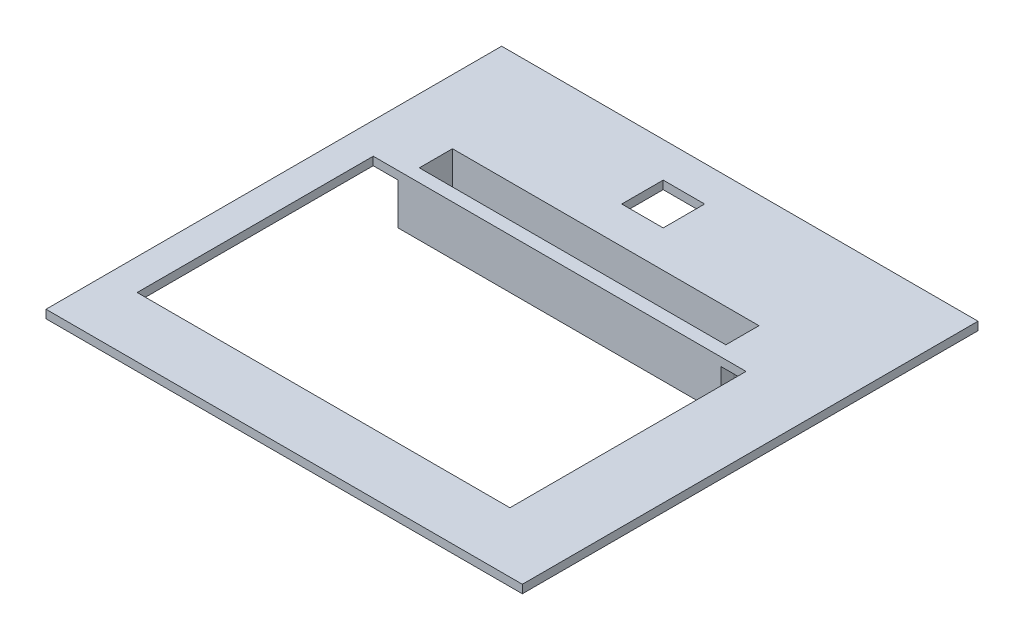
SolidWorks part; units mm, degrees
ref_plane "Front" through (0, 0, 0) normal (0, 0, 1) x (1, 0, 0)
ref_plane "Top" through (0, 0, 0) normal (0, 1, 0) x (1, 0, 0)
ref_plane "Right" through (0, 0, 0) normal (1, 0, 0) x (0, 0, -1)
sketch "Sketch2" plane through (0, 0, 0) normal (0, 1, 0) x (1, 0, 0)
  line L1 (57.5, 55) -> (-57.5, 55)
  line L2 (57.5, 55) -> (57.5, -55)
  line L3 (57.5, -55) -> (-57.5, -55)
  line L4 (-57.5, 55) -> (-57.5, -55)
  line L5 (57.5, 55) -> (-57.5, -55) construction
  line L6 (57.5, -55) -> (-57.5, 55) construction
  point P0 (0, 0)
  dimension "D1" = 110
  dimension "D2" = 115
extrude "Boss-Extrude1" add sketch "Sketch2" along normal blind 2
sketch "Sketch3" plane through (0, 2, 0) normal (0, 1, 0) x (1, 0, 0)
  line L0 (-57.5, -55) -> (57.5, -55) construction
  line L1 (-57.5, 55) -> (-57.5, -55) construction
  line L3 (-50, -40.5) -> (40, -40.5)
  line L4 (-50, -40.5) -> (-50, 16.5)
  line L5 (-50, 16.5) -> (40, 16.5)
  line L6 (40, -40.5) -> (40, 16.5)
  point P0 (-47, -44.5)
  point P5 (-47, -40.5)
  point P6 (-50, -40.5)
  dimension "D1" = 10.5
  dimension "D2" = 10.5
  dimension "D3" = 4
  dimension "D4" = 3
  dimension "D5" = 57
  dimension "D6" = 90
  dimension "D7" = 7.5
  dimension "D8" = 14.5
extrude "Cut-Extrude1" cut sketch "Sketch3" against normal through all both and the other way through all
sketch "Sketch4" plane through (0, 2, 0) normal (0, 1, 0) x (1, 0, 0)
  line L0 (-50, 16.5) -> (40, 16.5) construction
  line L1 (57.5, 55) -> (-57.5, 55) construction
  line L3 (-10, 40.75) -> (0, 40.75)
  line L4 (-10, 40.75) -> (-10, 30.75)
  line L5 (-10, 30.75) -> (0, 30.75)
  line L6 (0, 40.75) -> (0, 30.75)
  line L7 (-10, 40.75) -> (0, 30.75) construction
  line L8 (-10, 30.75) -> (0, 40.75) construction
  point P0 (-5, 16.5)
  point P1 (-5, 35.75)
  point P7 (-5, 35.75)
  dimension "D1" = 45
  dimension "D2" = 38.5
  dimension "D3" = 19.25
  dimension "D4" = 10
  dimension "D5" = 10
  dimension "D6" = 14.25
extrude "Cut-Extrude2" cut sketch "Sketch4" against normal blind 2
sketch "Sketch5" plane through (0, 2, 0) normal (0, 1, 0) x (1, 0, 0)
  line L0 (-10, 30.75) -> (0, 30.75) construction
  line L1 (-50, 16.5) -> (40, 16.5) construction
  line L2 (-57.5, 55) -> (-57.5, -55) construction
  line L3 (34, 19.625) -> (-44, 19.625)
  line L4 (34, 19.625) -> (34, 27.625)
  line L5 (34, 27.625) -> (-44, 27.625)
  line L6 (-44, 19.625) -> (-44, 27.625)
  line L7 (34, 19.625) -> (-44, 27.625) construction
  line L8 (34, 27.625) -> (-44, 19.625) construction
  line L9 (40, 16.5) -> (40, -40.5) construction
  line L10 (-50, -40.5) -> (-50, 16.5) construction
  point P0 (-5, 23.625)
  point P5 (-5, 23.625)
  dimension "D1" = 7.125
  dimension "D2" = 7.125
  dimension "D3" = 78
  dimension "D4" = 8
  dimension "D5" = 13.5
  dimension "D6" = 6
  dimension "D7" = 6
extrude "Cut-Extrude3" cut sketch "Sketch5" against normal through all
sketch "Sketch6" plane through (0, 0, 0) normal (0, -1, 0) x (-1, 0, 0)
  line L0 (-40, 16.5) -> (50, 16.5) construction
  line L1 (44, 19.625) -> (-34.0027, 19.625)
  line L2 (44, 19.625) -> (44, 16.5)
  line L3 (44, 16.5) -> (-34.0027, 16.5)
  line L4 (-34.0027, 19.625) -> (-34.0027, 16.5)
  dimension "D1" = 78.0027
extrude "Boss-Extrude3" add sketch "Sketch6" along normal blind 10
sketch "Sketch8" plane through (0, 0, 0) normal (0, -1, 0) x (-1, 0, 0)
  line L1 (-34, 27.625) -> (44, 27.625)
  line L2 (-34, 27.625) -> (-34, 28.625)
  line L3 (-34, 28.625) -> (44, 28.625)
  line L4 (44, 27.625) -> (44, 28.625)
  line L5 (-34, 28.625) -> (-19, 28.625)
  line L6 (-34, 28.625) -> (-34, 31.625)
  line L7 (-34, 31.625) -> (-19, 31.625)
  line L8 (-19, 28.625) -> (-19, 31.625)
  line L9 (44, 28.625) -> (29, 28.625)
  line L10 (44, 28.625) -> (44, 31.625)
  line L11 (44, 31.625) -> (29, 31.625)
  line L12 (29, 28.625) -> (29, 31.625)
  line L13 (44, 27.625) -> (42, 27.625)
  line L14 (44, 27.625) -> (44, 19.625)
  line L15 (44, 19.625) -> (42, 19.625)
  line L16 (42, 27.625) -> (42, 19.625)
  line L17 (-34, 27.625) -> (-32, 27.625)
  line L18 (-34, 27.625) -> (-34, 19.625)
  line L19 (-34, 19.625) -> (-32, 19.625)
  line L20 (-32, 27.625) -> (-32, 19.625)
  line M20 (-34, 27.625) -> (44, 27.625)
  dimension "D1" = 1
  dimension "D2" = 78
  dimension "D3" = 15
  dimension "D4" = 3
  dimension "D5" = 15
  dimension "D6" = 3
  dimension "D7" = 2
  dimension "D8" = 8
  dimension "D9" = 2
  dimension "D10" = 8
extrude "Boss-Extrude6" add sketch "Sketch8" along normal blind 10 contours L1 L4 L3 L2 M20 | L18 L17 L20 L19
sketch "Sketch10" plane through (0, 2, 0) normal (0, 1, 0) x (1, 0, 0)
  line L1 (34, 27.625) -> (32, 27.625)
  line L2 (34, 27.625) -> (34, 19.625)
  line L3 (34, 19.625) -> (32, 19.625)
  line L4 (32, 27.625) -> (32, 19.625)
  dimension "D1" = 8
  dimension "D2" = 2
extrude "Boss-Extrude7" add sketch "Sketch10" against normal blind 12
sketch "Sketch11" plane through (0, 2, 0) normal (0, 1, 0) x (1, 0, 0)
  line L0 (32, 27.625) -> (-44, 27.625) construction
  line L1 (-44, 19.625) -> (-42, 19.625)
  line L2 (-44, 19.625) -> (-44, 27.625)
  line L3 (-44, 27.625) -> (-42, 27.625)
  line L4 (-42, 19.625) -> (-42, 27.625)
  dimension "D1" = 8
  dimension "D2" = 2
extrude "Boss-Extrude8" add sketch "Sketch11" against normal blind 12
sketch "Sketch12" plane through (0, 0, 0) normal (0, -1, 0) x (-1, 0, 0)
  line L1 (-34, 28.625) -> (-19, 28.625)
  line L2 (-34, 28.625) -> (-34, 31.625)
  line L3 (-34, 31.625) -> (-19, 31.625)
  line L4 (-19, 28.625) -> (-19, 31.625)
  dimension "D1" = 15
  dimension "D2" = 3
extrude "Boss-Extrude9" add sketch "Sketch12" along normal blind 10
sketch "Sketch13" plane through (0, 0, 0) normal (0, -1, 0) x (-1, 0, 0)
  line L1 (44, 28.625) -> (29, 28.625)
  line L2 (44, 28.625) -> (44, 31.625)
  line L3 (44, 31.625) -> (29, 31.625)
  line L4 (29, 28.625) -> (29, 31.625)
  dimension "D1" = 15
  dimension "D2" = 3
extrude "Boss-Extrude10" add sketch "Sketch13" along normal blind 10
sketch "Sketch14" plane through (0, -10, 0) normal (0, -1, 0) x (-1, 0, 0)
  line L1 (-32, 19.625) -> (42, 19.625)
  line L2 (-32, 19.625) -> (-32, 27.625)
  line L3 (-32, 27.625) -> (42, 27.625)
  line L4 (42, 19.625) -> (42, 27.625)
extrude "Boss-Extrude11" add sketch "Sketch14" against normal blind 2 contours L2 L1 L4 L3
sketch "Sketch17" plane through (0, -8, 0) normal (0, 1, 0) x (1, 0, 0)
  line L0 (32, 19.625) -> (32, 27.625) construction
  line L1 (32, 27.625) -> (-42, 27.625) construction
  line L2 (-42, 19.625) -> (-42, 27.625) construction
  line L3 (32, 19.625) -> (-42, 19.625) construction
  circle A0 centre (25, 23.625) radius 2.375
  circle A1 centre (-35, 23.625) radius 2.375
  circle A2 centre (-26.43, 23.625) radius 2.375
  circle A3 centre (-17.86, 23.625) radius 2.375
  circle A4 centre (-0.72, 23.625) radius 2.375
  circle A5 centre (7.85, 23.625) radius 2.375
  circle A6 centre (16.42, 23.625) radius 2.375
  circle A7 centre (-9.29, 23.625) radius 2.375
  point P0 (25, 23.625)
  point P7 (-35, 23.625)
  point P12 (-26.43, 23.625)
  point P13 (-17.86, 23.625)
  point P14 (-0.72, 23.625)
  point P16 (7.85, 23.625)
  point P17 (16.42, 23.625)
  point P30 (-9.29, 23.625)
  dimension "D2" = 4
  dimension "D3" = 4.75
  dimension "D6" = 4.75
  dimension "D14" = 4.75
  dimension "D15" = 4.75
  dimension "D16" = 4.75
  dimension "D17" = 4.75
  dimension "D18" = 4.75
  dimension "D20" = 4
  dimension "D22" = 4.75
  dimension "D23" = 4.75
  dimension "D1" = 7
  dimension "D4" = 7
  dimension "D5" = 4
  dimension "D7" = 8.57
  dimension "D8" = 8.57
  dimension "D9" = 8.57
  dimension "D10" = 8.57
  dimension "D11" = 8.57
  dimension "D12" = 8.57
  dimension "D13" = 4
  dimension "D19" = 8.58
  dimension "D21" = 4
  dimension "D24" = 4
  dimension "D25" = 4
extrude "Cut-Extrude4" cut sketch "Sketch17" against normal through all
sketch "Sketch18" plane through (0, 2, 0) normal (0, 1, 0) x (1, 0, 0)
  line L1 (-10, 40.75) -> (0, 40.75)
  line L2 (-10, 40.75) -> (-10, 30.75)
  line L3 (-10, 30.75) -> (0, 30.75)
  line L4 (0, 40.75) -> (0, 30.75)
extrude "Boss-Extrude12" add sketch "Sketch18" against normal blind 2
sketch "Sketch20" plane through (0, 2, 0) normal (0, 1, 0) x (1, 0, 0)
  line L0 (-5, 16.5) -> (-5, 41.5)
  line L1 (-50, 16.5) -> (40, 16.5) construction
  line L3 (-10, 46.5) -> (0, 46.5)
  line L4 (-10, 46.5) -> (-10, 36.5)
  line L5 (-10, 36.5) -> (0, 36.5)
  line L6 (0, 46.5) -> (0, 36.5)
  line L7 (-10, 46.5) -> (0, 36.5) construction
  line L8 (-10, 36.5) -> (0, 46.5) construction
  dimension "D1" = 25
  dimension "D2" = 10
  dimension "D3" = 10
extrude "Cut-Extrude5" cut sketch "Sketch20" against normal through all both and the other way through all
